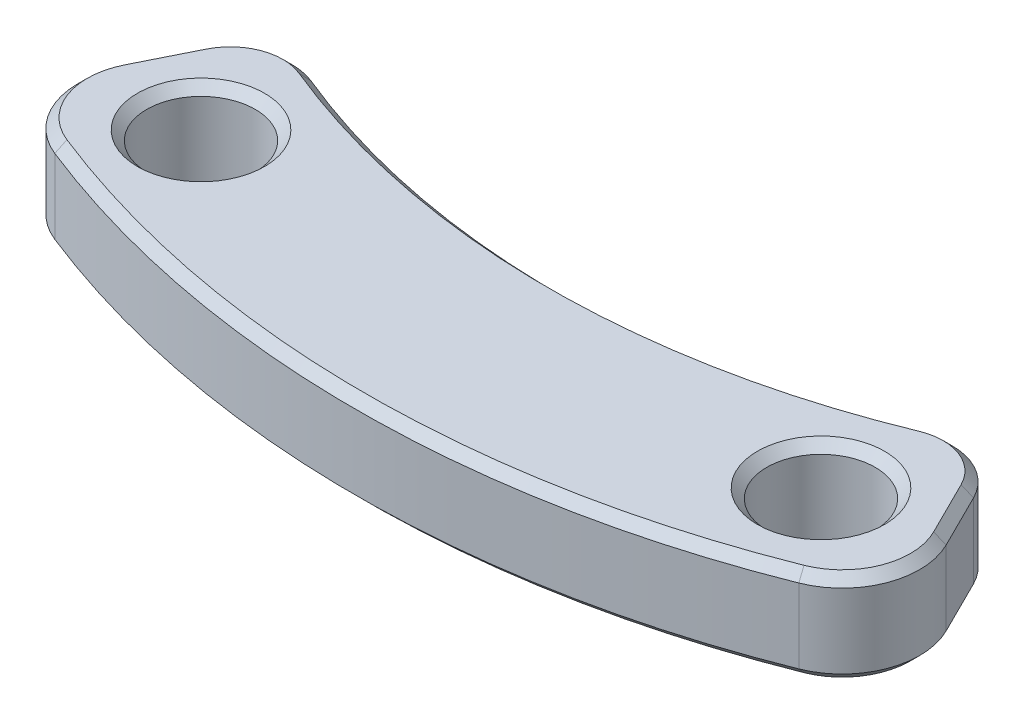
SolidWorks part; units mm, degrees
ref_plane "前视基准面" through (0, 0, 0) normal (0, 0, 1) x (1, 0, 0)
ref_plane "上视基准面" through (0, 0, 0) normal (0, 1, 0) x (1, 0, 0)
ref_plane "右视基准面" through (0, 0, 0) normal (1, 0, 0) x (0, 0, -1)
other "Configuration Table"
sketch "草图1" plane through (0, 0, 0) normal (0, 1, 0) x (1, 0, 0)
  line L0 (-5.6188, 0.8044) -> (14.3812, 0.8044) construction
  line L2 (4.3812, 41.8964) -> (4.3812, -12.1119) construction
  line L3 (-8.0581, 3.2866) -> (-8.9343, 1.5253)
  line L5 (16.8205, 3.2866) -> (17.6966, 1.5253)
  line L6 (-7.1992, 5.0132) -> (4.3812, 28.2919) construction
  line L7 (4.3812, 28.2919) -> (15.9615, 5.0132) construction
  circle A0 centre (-5.6188, 0.8044) radius 1.75
  circle A1 centre (14.3812, 0.8044) radius 1.75
  arc A2 (14.2692, 4.2455) -> (-5.5068, 4.2455) centre (4.3812, 28.2919) cw
  arc A3 (16.3814, -1.9115) -> (-7.619, -1.9115) centre (4.3812, 28.2919) cw
  arc A4 (16.3814, -1.9115) -> (17.6966, 1.5253) centre (15.4583, 0.4118) ccw
  arc A5 (-7.619, -1.9115) -> (-8.9343, 1.5253) centre (-6.6959, 0.4118) cw
  arc A6 (14.2692, 4.2455) -> (16.8205, 3.2866) centre (15.0298, 2.3958) cw
  arc A7 (-5.5068, 4.2455) -> (-8.0581, 3.2866) centre (-6.2674, 2.3958) ccw
  point P11 (0, 0)
  point P12 (18.8566, -0.8065)
  dimension "D1" = 3.5
  dimension "D2" = 3.5
  dimension "D3" = 26
  dimension "D4" = 32.5
  dimension "D7" = 2.5
  dimension "D8" = 2
  dimension "D5" = 20
  dimension "D6" = 29.25
extrude "凸台-拉伸1" add sketch "草图1" along normal blind 3
chamfer "倒角1" distance 0.3 angle 45 20 edges at (14.3812, 0, 0.9456) (14.3812, 3, 0.9456) (-5.6188, 0, 0.9456) (-5.6188, 3, 0.9456) (4.3812, 0, -2.2919) (-6.9711, 0, -4.2679) (15.7335, 0, -4.2679) (-8.4962, 0, -2.4059) (17.2585, 0, -2.4059) (-9.0308, 0, 0.4817) (17.7932, 0, 0.4817) (4.3812, 0, 4.2081) (4.3812, 3, 4.2081) (17.7932, 3, 0.4817) (-9.0308, 3, 0.4817) (17.2585, 3, -2.4059) (-8.4962, 3, -2.4059) (15.7335, 3, -4.2679) (-6.9711, 3, -4.2679) (4.3812, 3, -2.2919)
